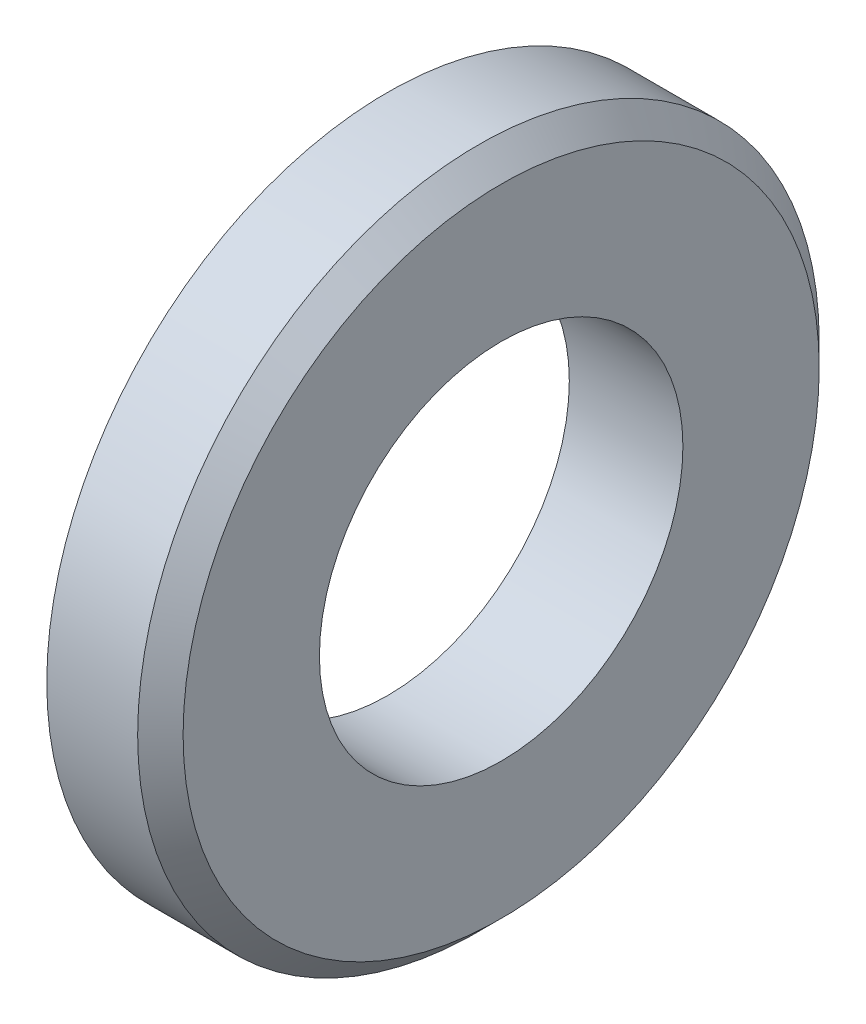
SolidWorks part; units mm, degrees
ref_plane "Front Plane" through (0, 0, 0) normal (0, 0, 1) x (1, 0, 0)
ref_plane "Top Plane" through (0, 0, 0) normal (0, 1, 0) x (1, 0, 0)
ref_plane "Right Plane" through (0, 0, 0) normal (1, 0, 0) x (0, 0, -1)
sketch "Sketch2" plane through (0, 0, 0) normal (1, 0, 0) x (0, 0, -1)
  circle A0 centre (0, 0) radius 30
extrude "Boss-Extrude1" add sketch "Sketch2" along normal blind 10 contours A0
chamfer "Chamfer1" distance 2 1 edges at (10, 0, -30)
sketch "Sketch3" plane through (10, 0, 0) normal (1, 0, 0) x (0, 0, -1)
  circle A0 centre (0, 0) radius 16
extrude "Cut-Extrude1" cut sketch "Sketch3" against normal blind 10
